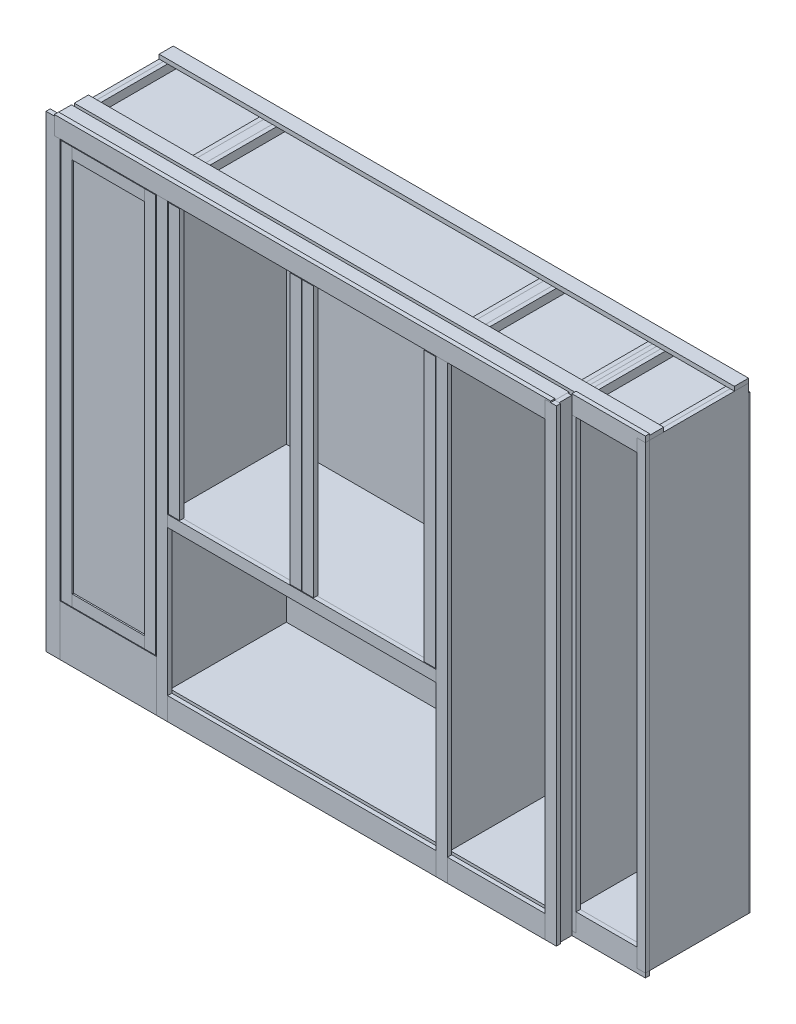
SolidWorks part; units mm, degrees
ref_plane "Front Plane" through (0, 0, 0) normal (0, 0, 1) x (1, 0, 0)
ref_plane "Top Plane" through (0, 0, 0) normal (0, 1, 0) x (1, 0, 0)
ref_plane "Right Plane" through (0, 0, 0) normal (1, 0, 0) x (0, 0, -1)
sketch "Sketch1" plane through (0, 0, 0) normal (0, 0, 1) x (1, 0, 0)
  line L0 (0, 0) -> (0, 1050.925) construction
  line L2 (-254, 19.05) -> (254, 19.05) construction
  line L3 (-254, 19.05) -> (-254, 2082.8) construction
  line L4 (-254, 2082.8) -> (254, 2082.8) construction
  line L5 (254, 19.05) -> (254, 2082.8) construction
  line L6 (-254, 19.05) -> (254, 2082.8) construction
  line L7 (-254, 2082.8) -> (254, 19.05) construction
  line L8 (-254, 2082.8) -> (-234.95, 2082.8)
  line L9 (-254, 2082.8) -> (-254, 19.05)
  line L10 (-254, 19.05) -> (-234.95, 19.05)
  line L11 (-234.95, 2082.8) -> (-234.95, 19.05)
  line L12 (254, 2082.8) -> (215.9, 2082.8)
  line L13 (254, 2082.8) -> (254, 19.05)
  line L14 (254, 19.05) -> (215.9, 19.05)
  line L15 (215.9, 2082.8) -> (215.9, 19.05)
  dimension "D1" = 19.05
  dimension "D2" = 2063.75
  dimension "D3" = 508
  dimension "D4" = 19.05
  dimension "D5" = 38.1
extrude "Boss-Extrude1" add sketch "Sketch1" against normal blind 520.7
sketch "Sketch2" plane through (0, 0, -520.7) normal (0, 0, -1) x (-1, 0, 0)
  line L1 (-215.9, 222.25) -> (-196.85, 222.25)
  line L2 (-215.9, 222.25) -> (-215.9, 19.05)
  line L3 (-215.9, 19.05) -> (-196.85, 19.05)
  line L4 (-196.85, 222.25) -> (-196.85, 19.05)
  line L6 (234.95, 19.05) -> (215.9, 19.05)
  line L7 (234.95, 19.05) -> (234.95, 222.25)
  line L8 (234.95, 222.25) -> (215.9, 222.25)
  line L9 (215.9, 19.05) -> (215.9, 222.25)
  dimension "D1" = 203.2
  dimension "D2" = 19.05
extrude "Boss-Extrude2" add sketch "Sketch2" against normal up to surface (520.7 mm away) separate body up to face at (-244.475, 1050.925, 0)
sketch "Sketch4" plane through (0, 0, -520.7) normal (0, 0, 1) x (1, 0, 0)
  line L1 (215.9, 222.25) -> (-234.95, 222.25)
  line L2 (215.9, 222.25) -> (215.9, 241.3)
  line L3 (215.9, 241.3) -> (-234.95, 241.3)
  line L4 (-234.95, 222.25) -> (-234.95, 241.3)
  dimension "D1" = 19.05
extrude "Boss-Extrude4" add sketch "Sketch4" along normal up to surface (520.7 mm away) separate body up to face at (234.95, 1050.925, 0)
sketch "Sketch5" plane through (0, 0, -520.7) normal (0, 0, 1) x (1, 0, 0)
  line L1 (215.9, 2082.8) -> (196.85, 2082.8)
  line L2 (215.9, 2082.8) -> (215.9, 2044.7)
  line L3 (215.9, 2044.7) -> (196.85, 2044.7)
  line L4 (196.85, 2082.8) -> (196.85, 2044.7)
  line L5 (-234.95, 2082.8) -> (-215.9, 2082.8)
  line L6 (-234.95, 2082.8) -> (-234.95, 2044.7)
  line L7 (-234.95, 2044.7) -> (-215.9, 2044.7)
  line L8 (-215.9, 2082.8) -> (-215.9, 2044.7)
  dimension "D1" = 19.05
  dimension "D2" = 38.1
extrude "Boss-Extrude5" add sketch "Sketch5" along normal up to surface (520.7 mm away) separate body up to face at (234.95, 1050.925, 0)
sketch "Sketch6" plane through (0, 0, -520.7) normal (0, 0, 1) x (1, 0, 0)
  line L1 (-234.95, 2044.7) -> (215.9, 2044.7)
  line L2 (-234.95, 2044.7) -> (-234.95, 2025.65)
  line L3 (-234.95, 2025.65) -> (215.9, 2025.65)
  line L4 (215.9, 2044.7) -> (215.9, 2025.65)
  dimension "D1" = 19.05
extrude "Boss-Extrude6" add sketch "Sketch6" along normal up to surface (520.7 mm away) separate body up to face at (234.95, 1050.925, 0)
sketch "Sketch8" plane through (0, 0, 0) normal (0, 0, 1) x (1, 0, 0)
  line L0 (1727.2, 0) -> (1727.2, 1050.925) construction
  line L1 (254, 19.05) -> (254, 2082.8) construction
  line L2 (1981.2, 19.05) -> (1473.2, 19.05) construction
  line L3 (1981.2, 19.05) -> (1981.2, 2082.8) construction
  line L4 (1981.2, 2082.8) -> (1473.2, 2082.8) construction
  line L5 (1473.2, 19.05) -> (1473.2, 2082.8) construction
  line L6 (1981.2, 19.05) -> (1473.2, 2082.8) construction
  line L7 (1981.2, 2082.8) -> (1473.2, 19.05) construction
  line L8 (3142.9795, 0) -> (-520.5672, 0) construction
  line L10 (1981.2, 2082.8) -> (1962.15, 2082.8)
  line L11 (1981.2, 2082.8) -> (1981.2, 19.05)
  line L12 (1981.2, 19.05) -> (1962.15, 19.05)
  line L13 (1962.15, 2082.8) -> (1962.15, 19.05)
  line L14 (1473.2, 2082.8) -> (1511.3, 2082.8)
  line L15 (1473.2, 2082.8) -> (1473.2, 19.05)
  line L16 (1473.2, 19.05) -> (1511.3, 19.05)
  line L17 (1511.3, 2082.8) -> (1511.3, 19.05)
  dimension "D1" = 19.05
  dimension "D2" = 508
  dimension "D3" = 1219.2
  dimension "D4" = 2063.75
  dimension "D5" = 19.05
  dimension "D6" = 38.1
extrude "Boss-Extrude7" add sketch "Sketch8" against normal blind 520.7 separate body
sketch "Sketch10" plane through (0, 0, -520.7) normal (0, 0, -1) x (-1, 0, 0)
  line L1 (-1530.35, 19.05) -> (-1511.3, 19.05)
  line L2 (-1530.35, 19.05) -> (-1530.35, 95.25)
  line L3 (-1530.35, 95.25) -> (-1511.3, 95.25)
  line L4 (-1511.3, 19.05) -> (-1511.3, 95.25)
  line L5 (-1943.1, 19.05) -> (-1962.15, 19.05)
  line L6 (-1943.1, 19.05) -> (-1943.1, 95.25)
  line L7 (-1943.1, 95.25) -> (-1962.15, 95.25)
  line L8 (-1962.15, 19.05) -> (-1962.15, 95.25)
  dimension "D1" = 19.05
  dimension "D2" = 76.2
extrude "Boss-Extrude8" add sketch "Sketch10" against normal up to surface (520.7 mm away) separate body up to face at (1971.675, 1050.925, 0)
sketch "Sketch12" plane through (0, 0, -520.7) normal (0, 0, -1) x (-1, 0, 0)
  line L1 (-1530.35, 2082.8) -> (-1511.3, 2082.8)
  line L2 (-1530.35, 2082.8) -> (-1530.35, 2044.7)
  line L3 (-1530.35, 2044.7) -> (-1511.3, 2044.7)
  line L4 (-1511.3, 2082.8) -> (-1511.3, 2044.7)
  line L5 (-1943.1, 2082.8) -> (-1962.15, 2082.8)
  line L6 (-1943.1, 2082.8) -> (-1943.1, 2044.7)
  line L7 (-1943.1, 2044.7) -> (-1962.15, 2044.7)
  line L8 (-1962.15, 2082.8) -> (-1962.15, 2044.7)
  dimension "D1" = 19.05
  dimension "D2" = 38.1
extrude "Boss-Extrude9" add sketch "Sketch12" against normal up to surface (520.7 mm away) separate body up to face at (1971.675, 1050.925, 0)
sketch "Sketch13" plane through (0, 0, -520.7) normal (0, 0, -1) x (-1, 0, 0)
  line L0 (-1962.15, 2082.8) -> (-1962.15, 19.05) construction
  line L1 (-1511.3, 95.25) -> (-1962.15, 95.25)
  line L2 (-1511.3, 95.25) -> (-1511.3, 114.3)
  line L3 (-1511.3, 114.3) -> (-1962.15, 114.3)
  line L4 (-1962.15, 95.25) -> (-1962.15, 114.3)
  dimension "D1" = 19.05
extrude "Boss-Extrude10" add sketch "Sketch13" against normal up to surface (520.7 mm away) separate body up to face at (1492.25, 1050.925, 0)
sketch "Sketch14" plane through (0, 0, -520.7) normal (0, 0, -1) x (-1, 0, 0)
  line L0 (-1962.15, 2082.8) -> (-1962.15, 19.05) construction
  line L1 (-1511.3, 2044.7) -> (-1962.15, 2044.7)
  line L2 (-1511.3, 2044.7) -> (-1511.3, 2025.65)
  line L3 (-1511.3, 2025.65) -> (-1962.15, 2025.65)
  line L4 (-1962.15, 2044.7) -> (-1962.15, 2025.65)
  dimension "D1" = 19.05
extrude "Boss-Extrude11" add sketch "Sketch14" against normal up to surface (520.7 mm away) separate body up to face at (1971.675, 1050.925, 0)
sketch "Sketch15" plane through (0, 0, -520.7) normal (0, 0, -1) x (-1, 0, 0)
  line L1 (-254, 19.05) -> (-273.05, 19.05)
  line L2 (-254, 19.05) -> (-254, 95.25)
  line L3 (-254, 95.25) -> (-273.05, 95.25)
  line L4 (-273.05, 19.05) -> (-273.05, 95.25)
  line L5 (-1473.2, 19.05) -> (-1454.15, 19.05)
  line L6 (-1473.2, 19.05) -> (-1473.2, 95.25)
  line L7 (-1473.2, 95.25) -> (-1454.15, 95.25)
  line L8 (-1454.15, 19.05) -> (-1454.15, 95.25)
  line L9 (-1473.2, 2082.8) -> (-1454.15, 2082.8)
  line L10 (-1473.2, 2082.8) -> (-1473.2, 2044.7)
  line L11 (-1473.2, 2044.7) -> (-1454.15, 2044.7)
  line L12 (-1454.15, 2082.8) -> (-1454.15, 2044.7)
  line L13 (-254, 2082.8) -> (-273.05, 2082.8)
  line L14 (-254, 2082.8) -> (-254, 2044.7)
  line L15 (-254, 2044.7) -> (-273.05, 2044.7)
  line L16 (-273.05, 2082.8) -> (-273.05, 2044.7)
  dimension "D1" = 19.05
  dimension "D2" = 38.1
  dimension "D3" = 76.2
extrude "Boss-Extrude12" add sketch "Sketch15" against normal up to surface (520.7 mm away) separate body up to face at (1492.25, 1050.925, 0)
sketch "Sketch16" plane through (0, 0, -520.7) normal (0, 0, -1) x (-1, 0, 0)
  line L0 (-254, 19.05) -> (-254, 2082.8) construction
  line L1 (-1473.2, 2044.7) -> (-254, 2044.7)
  line L2 (-1473.2, 2044.7) -> (-1473.2, 2025.65)
  line L3 (-1473.2, 2025.65) -> (-254, 2025.65)
  line L4 (-254, 2044.7) -> (-254, 2025.65)
  line L6 (-1473.2, 95.25) -> (-254, 95.25)
  line L7 (-1473.2, 95.25) -> (-1473.2, 114.3)
  line L8 (-1473.2, 114.3) -> (-254, 114.3)
  line L9 (-254, 95.25) -> (-254, 114.3)
  dimension "D1" = 19.05
  dimension "D2" = 19.05
extrude "Boss-Extrude13" add sketch "Sketch16" against normal up to surface (520.7 mm away) separate body up to face at (1492.25, 1050.925, 0)
sketch "Sketch17" plane through (0, 0, -520.7) normal (0, 0, -1) x (-1, 0, 0)
  line L0 (-254, 19.05) -> (-254, 2082.8) construction
  line L1 (-1473.2, 2025.65) -> (-254, 2025.65) construction
  line L2 (-1473.2, 2025.65) -> (-1473.2, 806.45) construction
  line L3 (-1473.2, 806.45) -> (-254, 806.45) construction
  line L4 (-254, 2025.65) -> (-254, 806.45) construction
  line L6 (-1473.2, 806.45) -> (-254, 806.45)
  line L7 (-1473.2, 806.45) -> (-1473.2, 787.4)
  line L8 (-1473.2, 787.4) -> (-254, 787.4)
  line L9 (-254, 806.45) -> (-254, 787.4)
  dimension "D1" = 1219.2
  dimension "D2" = 19.05
extrude "Boss-Extrude14" add sketch "Sketch17" against normal up to surface (520.7 mm away) separate body up to face at (1492.25, 1050.925, 0)
sketch "Sketch25" plane through (0, 0, -520.7) normal (0, 0, -1) x (-1, 0, 0)
  line L1 (-1981.2, 2082.8) -> (-2000.25, 2082.8)
  line L2 (-1981.2, 2082.8) -> (-1981.2, 19.05)
  line L3 (-1981.2, 19.05) -> (-2000.25, 19.05)
  line L4 (-2000.25, 2082.8) -> (-2000.25, 19.05)
  dimension "D1" = 19.05
extrude "Boss-Extrude22" add sketch "Sketch25" against normal blind 444.5 separate body
sketch "Sketch26" plane through (0, 0, -520.7) normal (0, 0, 1) x (1, 0, 0)
  line L1 (2000.25, 2082.8) -> (2330.45, 2082.8) construction
  line L2 (2000.25, 2082.8) -> (2000.25, 19.05) construction
  line L3 (2000.25, 19.05) -> (2330.45, 19.05) construction
  line L4 (2330.45, 2082.8) -> (2330.45, 19.05) construction
  line L5 (2330.45, 2082.8) -> (2311.4, 2082.8)
  line L6 (2330.45, 2082.8) -> (2330.45, 19.05)
  line L7 (2330.45, 19.05) -> (2311.4, 19.05)
  line L8 (2311.4, 2082.8) -> (2311.4, 19.05)
  dimension "D1" = 330.2
  dimension "D2" = 2063.75
  dimension "D3" = 19.05
extrude "Boss-Extrude23" add sketch "Sketch26" along normal blind 444.5 separate body
sketch "Sketch27" plane through (0, 0, -520.7) normal (0, 0, -1) x (-1, 0, 0)
  line L1 (-2000.25, 2082.8) -> (-2019.3, 2082.8)
  line L2 (-2000.25, 2082.8) -> (-2000.25, 2044.7)
  line L3 (-2000.25, 2044.7) -> (-2019.3, 2044.7)
  line L4 (-2019.3, 2082.8) -> (-2019.3, 2044.7)
  line L5 (-2311.4, 2082.8) -> (-2292.35, 2082.8)
  line L6 (-2311.4, 2082.8) -> (-2311.4, 2044.7)
  line L7 (-2311.4, 2044.7) -> (-2292.35, 2044.7)
  line L8 (-2292.35, 2082.8) -> (-2292.35, 2044.7)
  line L9 (-2000.25, 19.05) -> (-2019.3, 19.05)
  line L10 (-2000.25, 19.05) -> (-2000.25, 82.55)
  line L11 (-2000.25, 82.55) -> (-2019.3, 82.55)
  line L12 (-2019.3, 19.05) -> (-2019.3, 82.55)
  line L13 (-2311.4, 19.05) -> (-2292.35, 19.05)
  line L14 (-2311.4, 19.05) -> (-2311.4, 82.55)
  line L15 (-2311.4, 82.55) -> (-2292.35, 82.55)
  line L16 (-2292.35, 19.05) -> (-2292.35, 82.55)
  dimension "D1" = 19.05
  dimension "D2" = 38.1
  dimension "D3" = 63.5
extrude "Boss-Extrude24" add sketch "Sketch27" against normal up to surface (444.5 mm away) separate body up to face at (2320.925, 1050.925, -76.2)
sketch "Sketch28" plane through (0, 0, -520.7) normal (0, 0, -1) x (-1, 0, 0)
  line L0 (-2311.4, 2082.8) -> (-2311.4, 19.05) construction
  line L1 (-2000.25, 82.55) -> (-2311.4, 82.55)
  line L2 (-2000.25, 82.55) -> (-2000.25, 101.6)
  line L3 (-2000.25, 101.6) -> (-2311.4, 101.6)
  line L4 (-2311.4, 82.55) -> (-2311.4, 101.6)
  line L6 (-2000.25, 2044.7) -> (-2311.4, 2044.7)
  line L7 (-2000.25, 2044.7) -> (-2000.25, 2025.65)
  line L8 (-2000.25, 2025.65) -> (-2311.4, 2025.65)
  line L9 (-2311.4, 2044.7) -> (-2311.4, 2025.65)
  dimension "D1" = 19.05
extrude "Boss-Extrude25" add sketch "Sketch28" against normal up to surface (444.5 mm away) separate body up to face at (2320.925, 1050.925, -76.2)
sketch "Sketch19" plane through (0, 0, 0) normal (0, 0, 1) x (1, 0, 0)
  line L0 (1981.2, 19.05) -> (1981.2, 2082.8) construction
  line L1 (-254, 19.05) -> (1981.2, 19.05)
  line L2 (-254, 19.05) -> (-254, 0)
  line L3 (-254, 0) -> (1981.2, 0)
  line L4 (1981.2, 19.05) -> (1981.2, 0)
  line L8 (-254, 2082.8) -> (1981.2, 2082.8)
  line L9 (-254, 2082.8) -> (-254, 2101.85)
  line L10 (-254, 2101.85) -> (1981.2, 2101.85)
  line L11 (1981.2, 2082.8) -> (1981.2, 2101.85)
  dimension "D1" = 19.05
  dimension "D2" = 19.05
extrude "Boss-Extrude16" add sketch "Sketch19" against normal blind 63.5 separate body
sketch "Sketch20" plane through (0, 0, 0) normal (0, 0, 1) x (1, 0, 0)
  line L1 (-254, 2082.8) -> (-273.05, 2082.8)
  line L2 (-254, 2082.8) -> (-254, 0)
  line L3 (-254, 0) -> (-273.05, 0)
  line L4 (-273.05, 2082.8) -> (-273.05, 0)
  dimension "D1" = 19.05
extrude "Boss-Extrude17" add sketch "Sketch20" against normal blind 63.5 separate body
sketch "Sketch21" plane through (0, 0, 0) normal (0, 0, 1) x (1, 0, 0)
  line L0 (-234.95, 19.05) -> (-234.95, 2082.8) construction
  line L1 (-222.25, 2101.85) -> (-285.75, 2101.85)
  line L2 (-222.25, 2101.85) -> (-222.25, 0)
  line L3 (-222.25, 0) -> (-285.75, 0)
  line L4 (-285.75, 2101.85) -> (-285.75, 0)
  line L5 (-273.05, 0) -> (-254, 0) construction
  line L6 (1981.2, 2101.85) -> (-254, 2101.85) construction
  dimension "D1" = 12.7
  dimension "D2" = 63.5
extrude "Boss-Extrude18" add sketch "Sketch21" along normal blind 19.05 separate body
sketch "Sketch22" plane through (0, 0, 0) normal (0, 0, 1) x (1, 0, 0)
  line L0 (234.95, 1982.001) -> (234.95, 1850.1699) construction
  line L1 (254, 2082.8) -> (215.9, 2082.8) construction
  line L2 (1492.25, 2082.8) -> (1492.25, -47917.2) construction
  line L3 (1511.3, 2082.8) -> (1473.2, 2082.8) construction
  line L4 (1981.2, 2082.8) -> (1981.2, 52082.8) construction
  line L6 (-222.25, 0) -> (-222.25, 2101.85) construction
  line L7 (209.55, 0) -> (260.35, 0)
  line L8 (209.55, 0) -> (209.55, 2101.85)
  line L9 (209.55, 2101.85) -> (260.35, 2101.85)
  line L10 (260.35, 0) -> (260.35, 2101.85)
  line L11 (209.55, 0) -> (260.35, 2101.85) construction
  line L12 (209.55, 2101.85) -> (260.35, 0) construction
  line L13 (1466.85, 0) -> (1517.65, 0)
  line L14 (1466.85, 0) -> (1466.85, 2101.85)
  line L15 (1466.85, 2101.85) -> (1517.65, 2101.85)
  line L16 (1517.65, 0) -> (1517.65, 2101.85)
  line L17 (1466.85, 0) -> (1517.65, 2101.85) construction
  line L18 (1466.85, 2101.85) -> (1517.65, 0) construction
  line L19 (1955.8, 0) -> (2006.6, 0)
  line L20 (1955.8, 0) -> (1955.8, 2101.85)
  line L21 (1955.8, 2101.85) -> (2006.6, 2101.85)
  line L22 (2006.6, 0) -> (2006.6, 2101.85)
  line L23 (1955.8, 0) -> (2006.6, 2101.85) construction
  line L24 (1955.8, 2101.85) -> (2006.6, 0) construction
  line L25 (-254, 0) -> (1981.2, 0) construction
  line L28 (1981.2, 19.05) -> (1981.2, 2082.8) construction
  point P6 (1492.25, 2082.8)
  point P12 (234.95, 1050.925)
  point P17 (1492.25, 1050.925)
  point P22 (1981.2, 1050.925)
  point P27 (234.95, 2082.8)
  dimension "D1" = 50.8
  dimension "D2" = 0
  dimension "D4" = 25.4
extrude "Boss-Extrude19" add sketch "Sketch22" along normal blind 19.05 separate body
sketch "Sketch23" plane through (0, 0, 0) normal (0, 0, 1) x (1, 0, 0)
  line L0 (209.55, 0) -> (260.35, 0) construction
  line L1 (-273.05, 0) -> (234.95, 0)
  line L2 (-273.05, 0) -> (-273.05, 228.6)
  line L3 (-273.05, 228.6) -> (234.95, 228.6)
  line L4 (234.95, 0) -> (234.95, 228.6)
  point P5 (234.95, 0)
  dimension "D1" = 228.6
extrude "Boss-Extrude20" add sketch "Sketch23" along normal blind 19.05 separate body
sketch "Sketch24" plane through (0, 0, 0) normal (0, 0, 1) x (1, 0, 0)
  line L0 (209.55, 0) -> (260.35, 0) construction
  line L1 (234.95, 0) -> (1981.2, 0)
  line L2 (234.95, 0) -> (234.95, 101.6)
  line L3 (234.95, 101.6) -> (1981.2, 101.6)
  line L4 (1981.2, 0) -> (1981.2, 101.6)
  line L5 (1981.2, 19.05) -> (1981.2, 2082.8) construction
  line L6 (863.6, -193.55) -> (863.6, 49806.45) construction
  line L7 (1981.2, 2025.65) -> (-248.3733, 2025.65)
  line L8 (1981.2, 2025.65) -> (1981.2, 2108.2)
  line L9 (1981.2, 2108.2) -> (-248.3733, 2108.2)
  line L10 (-248.3733, 2025.65) -> (-248.3733, 2108.2)
  line L11 (2006.6, 2101.85) -> (1955.8, 2101.85) construction
  line L12 (-746, 781.05) -> (49254, 781.05) construction
  line L14 (254, 806.45) -> (1473.2, 806.45) construction
  line L15 (1492.25, 1082.8) -> (1492.25, 51082.8) construction
  line L16 (234.95, 755.65) -> (1492.25, 755.65)
  line L17 (234.95, 755.65) -> (234.95, 806.45)
  line L18 (234.95, 806.45) -> (1492.25, 806.45)
  line L19 (1492.25, 755.65) -> (1492.25, 806.45)
  line L20 (234.95, 755.65) -> (1492.25, 806.45) construction
  line L21 (234.95, 806.45) -> (1492.25, 755.65) construction
  line L22 (1511.3, 2082.8) -> (1473.2, 2082.8) construction
  line L23 (234.95, 1082.8) -> (234.95, 51082.8) construction
  line L24 (254, 2082.8) -> (215.9, 2082.8) construction
  point P12 (1981.2, 2101.85)
  point P21 (863.6, 781.05)
  point P25 (863.6, 806.45)
  point P35 (1492.25, 2082.8)
  point P40 (234.95, 2082.8)
  dimension "D1" = 101.6
  dimension "D2" = 0
  dimension "D3" = 82.55
  dimension "D4" = 50.8
  dimension "D5" = 0
extrude "Boss-Extrude21" add sketch "Sketch24" along normal blind 19.05 separate body
sketch "Sketch29" plane through (0, 0, -76.2) normal (0, 0, 1) x (1, 0, 0)
  line L6 (2330.45, 2082.8) -> (2292.35, 2082.8)
  line L7 (2330.45, 2082.8) -> (2330.45, 19.05)
  line L8 (2330.45, 19.05) -> (2292.35, 19.05)
  line L9 (2292.35, 2082.8) -> (2292.35, 19.05)
  line L10 (1981.2, 2082.8) -> (2019.3, 2082.8)
  line L11 (1981.2, 2082.8) -> (1981.2, 19.05)
  line L12 (1981.2, 19.05) -> (2019.3, 19.05)
  line L13 (2019.3, 2082.8) -> (2019.3, 19.05)
  dimension "D1" = 38.1
extrude "Boss-Extrude26" add sketch "Sketch29" along normal blind 19.05 separate body
sketch "Sketch30" plane through (0, 0, -76.2) normal (0, 0, 1) x (1, 0, 0)
  line L1 (2000.25, 2025.65) -> (2330.45, 2025.65)
  line L2 (2000.25, 2025.65) -> (2000.25, 2108.2)
  line L3 (2000.25, 2108.2) -> (2330.45, 2108.2)
  line L4 (2330.45, 2025.65) -> (2330.45, 2108.2)
  line L5 (2000.25, 101.6) -> (2330.45, 101.6)
  line L6 (2000.25, 101.6) -> (2000.25, 0)
  line L7 (2000.25, 0) -> (2330.45, 0)
  line L8 (2330.45, 101.6) -> (2330.45, 0)
  line L9 (2330.45, 19.05) -> (2330.45, 2082.8) construction
  line L10 (2330.45, 19.05) -> (2330.45, 2082.8) construction
  dimension "D1" = 101.6
  dimension "D2" = 82.55
extrude "Boss-Extrude27" add sketch "Sketch30" along normal blind 19.05 separate body
sketch "Sketch31" plane through (1981.2, 0, 0) normal (1, 0, 0) x (0, 0, -1)
  line L1 (0, 2101.85) -> (57.15, 2101.85)
  line L2 (0, 2101.85) -> (0, 0)
  line L3 (0, 0) -> (57.15, 0)
  line L4 (57.15, 2101.85) -> (57.15, 0)
extrude "Boss-Extrude28" add sketch "Sketch31" along normal blind 19.05 separate body
sketch "Sketch33" plane through (0, 0, 0) normal (0, 0, 1) x (1, 0, 0)
  line L0 (-248.3733, 2025.65) -> (1981.2, 2025.65) construction
  line L1 (-222.25, 2025.65) -> (209.55, 2025.65) construction
  line L2 (-222.25, 2025.65) -> (-222.25, 228.6) construction
  line L3 (-222.25, 228.6) -> (209.55, 228.6) construction
  line L4 (209.55, 2025.65) -> (209.55, 228.6) construction
  line L5 (-222.25, 0) -> (-222.25, 2101.85) construction
  line L6 (209.55, 2101.85) -> (209.55, 0) construction
  line L7 (234.95, 228.6) -> (-273.05, 228.6) construction
  line L8 (-219.075, 2022.475) -> (206.375, 2022.475) construction
  line L9 (206.375, 2022.475) -> (206.375, 231.775) construction
  line L10 (-219.075, 231.775) -> (206.375, 231.775) construction
  line L11 (-219.075, 2022.475) -> (-219.075, 231.775) construction
  line L13 (-219.075, 2022.475) -> (-168.275, 2022.475)
  line L14 (-219.075, 2022.475) -> (-219.075, 231.775)
  line L15 (-219.075, 231.775) -> (-168.275, 231.775)
  line L16 (-168.275, 2022.475) -> (-168.275, 231.775)
  line L17 (206.375, 231.775) -> (155.575, 231.775)
  line L18 (206.375, 231.775) -> (206.375, 2022.475)
  line L19 (206.375, 2022.475) -> (155.575, 2022.475)
  line L20 (155.575, 231.775) -> (155.575, 2022.475)
  dimension "D2" = 50.8
  dimension "D1" = 3.175
extrude "Boss-Extrude29" add sketch "Sketch33" along normal blind 19.05 separate body
sketch "Sketch34" plane through (0, 0, 0) normal (0, 0, 1) x (1, 0, 0)
  line L1 (-180.975, 2022.475) -> (168.275, 2022.475)
  line L2 (-180.975, 2022.475) -> (-180.975, 1971.675)
  line L3 (-180.975, 1971.675) -> (168.275, 1971.675)
  line L4 (168.275, 2022.475) -> (168.275, 1971.675)
  line L6 (-180.975, 231.775) -> (168.275, 231.775)
  line L7 (-180.975, 231.775) -> (-180.975, 282.575)
  line L8 (-180.975, 282.575) -> (168.275, 282.575)
  line L9 (168.275, 231.775) -> (168.275, 282.575)
  line L10 (-168.275, 231.775) -> (-168.275, 2022.475) construction
  line L11 (155.575, 2022.475) -> (155.575, 231.775) construction
  dimension "D1" = 50.8
  dimension "D2" = 12.7
  dimension "D3" = 12.7
extrude "Boss-Extrude30" add sketch "Sketch34" along normal blind 19.05 separate body
sketch "Sketch36" plane through (0, 2022.475, 0) normal (0, 1, 0) x (1, 0, 0)
  line L0 (-168.275, -19.05) -> (-168.275, 0) construction
  line L1 (-168.275, -6.35) -> (-180.975, -6.35)
  line L2 (-168.275, -6.35) -> (-168.275, -12.7)
  line L3 (-168.275, -12.7) -> (-180.975, -12.7)
  line L4 (-180.975, -6.35) -> (-180.975, -12.7)
  line L5 (-1168.275, -9.525) -> (48831.725, -9.525) construction
  line L6 (-6.35, -19.05) -> (-6.35, 0) construction
  line L7 (168.275, -19.05) -> (-180.975, -19.05) construction
  line L8 (168.275, 0) -> (-180.975, 0) construction
  line L9 (168.275, -6.35) -> (168.275, -12.7)
  line L10 (155.575, -12.7) -> (168.275, -12.7)
  line L11 (155.575, -6.35) -> (155.575, -12.7)
  line L12 (155.575, -6.35) -> (168.275, -6.35)
  point P9 (-168.275, -9.525)
  dimension "D1" = 6.35
  dimension "D2" = 12.7
extrude "Cut-Extrude1" cut sketch "Sketch36" against normal through all
sketch "Sketch37" plane through (0, 2022.475, 0) normal (0, 1, 0) x (1, 0, 0)
  line L1 (-168.275, -6.35) -> (-180.975, -6.35)
  line L2 (-168.275, -6.35) -> (-168.275, 0)
  line L3 (-168.275, 0) -> (-180.975, 0)
  line L4 (-180.975, -6.35) -> (-180.975, 0)
  line L6 (-168.275, -12.7) -> (-180.975, -12.7)
  line L7 (-168.275, -12.7) -> (-168.275, -19.05)
  line L8 (-168.275, -19.05) -> (-180.975, -19.05)
  line L9 (-180.975, -12.7) -> (-180.975, -19.05)
  line L10 (-180.975, -6.35) -> (-180.975, -12.7) construction
  line L12 (168.275, 0) -> (-180.975, 0) construction
  line L13 (168.275, -19.05) -> (-180.975, -19.05) construction
  line L14 (-6.35, -19.05) -> (-6.35, 0) construction
  line L15 (168.275, -12.7) -> (168.275, -19.05)
  line L16 (155.575, -19.05) -> (168.275, -19.05)
  line L17 (155.575, -12.7) -> (155.575, -19.05)
  line L18 (155.575, -12.7) -> (168.275, -12.7)
  line L19 (168.275, -6.35) -> (168.275, 0)
  line L20 (155.575, 0) -> (168.275, 0)
  line L21 (155.575, -6.35) -> (155.575, 0)
  line L22 (155.575, -6.35) -> (168.275, -6.35)
extrude "Cut-Extrude2" cut sketch "Sketch37" against normal through all
sketch "Sketch39" plane through (-180.975, 0, 0) normal (-1, 0, 0) x (0, 0, 1)
  line L0 (6.35, 1971.675) -> (6.35, 2022.475) construction
  line L1 (12.7, 1971.675) -> (6.35, 1971.675)
  line L2 (12.7, 1971.675) -> (12.7, 1984.375)
  line L3 (12.7, 1984.375) -> (6.35, 1984.375)
  line L4 (6.35, 1971.675) -> (6.35, 1984.375)
  line L5 (6.35, 231.775) -> (6.35, 282.575) construction
  line L6 (12.7, 282.575) -> (6.35, 282.575)
  line L7 (12.7, 282.575) -> (12.7, 269.875)
  line L8 (12.7, 269.875) -> (6.35, 269.875)
  line L9 (6.35, 282.575) -> (6.35, 269.875)
  dimension "D1" = 12.7
  dimension "D2" = 12.7
extrude "Cut-Extrude3" cut sketch "Sketch39" against normal through all
sketch "Sketch40" plane through (0, 0, 6.35) normal (0, 0, -1) x (-1, 0, 0)
  line L1 (180.975, 1984.375) -> (-168.275, 1984.375)
  line L2 (180.975, 1984.375) -> (180.975, 269.875)
  line L3 (180.975, 269.875) -> (-168.275, 269.875)
  line L4 (-168.275, 1984.375) -> (-168.275, 269.875)
extrude "Boss-Extrude31" add sketch "Sketch40" against normal up to surface (6.35 mm away) separate body up to face at (-6.35, 276.225, 12.7)
sketch "Sketch41" plane through (0, 0, -520.7) normal (0, 0, -1) x (-1, 0, 0)
  line L0 (254, 2082.8) -> (254, 19.05) construction
  line L1 (254, 2044.7) -> (-2330.45, 2044.7)
  line L2 (254, 2044.7) -> (254, 19.05)
  line L3 (254, 19.05) -> (-2330.45, 19.05)
  line L4 (-2330.45, 2044.7) -> (-2330.45, 19.05)
  line L5 (-2330.45, 19.05) -> (-2330.45, 2082.8) construction
extrude "Boss-Extrude32" add sketch "Sketch41" along normal blind 6.35 separate body
sketch "Sketch42" plane through (0, 2082.8, 0) normal (0, 1, 0) x (1, 0, 0)
  line L0 (2330.45, 76.2) -> (2330.45, 520.7) construction
  line L1 (-254, 520.7) -> (2330.45, 520.7)
  line L2 (-254, 520.7) -> (-254, 457.2)
  line L3 (-254, 457.2) -> (2330.45, 457.2)
  line L4 (2330.45, 520.7) -> (2330.45, 457.2)
  line L5 (-254, 520.7) -> (-254, 0) construction
  line L6 (2330.45, 76.2) -> (-254, 76.2)
  line L7 (2330.45, 76.2) -> (2330.45, 139.7)
  line L8 (2330.45, 139.7) -> (-254, 139.7)
  line L9 (-254, 76.2) -> (-254, 139.7)
  dimension "D1" = 63.5
extrude "Boss-Extrude33" add sketch "Sketch42" along normal blind 19.05 separate body
sketch "Sketch43" plane through (0, 0, 0) normal (0, 0, 1) x (1, 0, 0)
  line L0 (260.35, 0) -> (260.35, 2101.85) construction
  line L1 (260.35, 2025.65) -> (1466.85, 2025.65) construction
  line L2 (260.35, 2025.65) -> (260.35, 806.45) construction
  line L3 (260.35, 806.45) -> (1466.85, 806.45) construction
  line L4 (1466.85, 2025.65) -> (1466.85, 806.45) construction
  line L5 (-248.3733, 2025.65) -> (1981.2, 2025.65) construction
  line L6 (254, 806.45) -> (1473.2, 806.45) construction
  line L7 (1466.85, 2101.85) -> (1466.85, 0) construction
  line L8 (263.525, 2022.475) -> (263.525, 809.625) construction
  line L9 (263.525, 809.625) -> (1463.675, 809.625) construction
  line L10 (1463.675, 2022.475) -> (1463.675, 809.625) construction
  line L11 (263.525, 2022.475) -> (1463.675, 2022.475) construction
  line L13 (1463.675, 2022.475) -> (1412.875, 2022.475)
  line L14 (1463.675, 2022.475) -> (1463.675, 809.625)
  line L15 (1463.675, 809.625) -> (1412.875, 809.625)
  line L16 (1412.875, 2022.475) -> (1412.875, 809.625)
  line L17 (263.525, 2022.475) -> (314.325, 2022.475)
  line L18 (263.525, 2022.475) -> (263.525, 809.625)
  line L19 (263.525, 809.625) -> (314.325, 809.625)
  line L20 (314.325, 2022.475) -> (314.325, 809.625)
  dimension "D2" = 50.8
  dimension "D1" = 3.175
extrude "Boss-Extrude34" add sketch "Sketch43" along normal blind 19.05 separate body
sketch "Sketch44" plane through (0, 0, 0) normal (0, 0, 1) x (1, 0, 0)
  line L0 (863.6, -193.55) -> (863.6, 49806.45) construction
  line L1 (1492.25, 806.45) -> (234.95, 806.45) construction
  line L4 (865.1875, -193.55) -> (865.1875, 49806.45) construction
  line L5 (862.0125, -193.55) -> (862.0125, 49806.45) construction
  line L7 (314.325, 2022.475) -> (1412.875, 2022.475) construction
  line L8 (314.325, 2022.475) -> (314.325, 809.625) construction
  line L9 (314.325, 809.625) -> (1412.875, 809.625) construction
  line L10 (1412.875, 2022.475) -> (1412.875, 809.625) construction
  line L11 (862.0125, 2022.475) -> (811.2125, 2022.475)
  line L12 (862.0125, 2022.475) -> (862.0125, 809.625)
  line L13 (862.0125, 809.625) -> (811.2125, 809.625)
  line L14 (811.2125, 2022.475) -> (811.2125, 809.625)
  line L15 (865.1875, 2022.475) -> (915.9875, 2022.475)
  line L16 (865.1875, 2022.475) -> (865.1875, 809.625)
  line L17 (865.1875, 809.625) -> (915.9875, 809.625)
  line L18 (915.9875, 2022.475) -> (915.9875, 809.625)
  point P5 (863.6, 806.45)
  dimension "D1" = 1.5875
  dimension "D3" = 50.8
  dimension "D2" = 1.5875
extrude "Boss-Extrude35" add sketch "Sketch44" along normal blind 19.05 separate body
equation "\"ply_cabinet_thickness\"= 0.75"
equation "\"ply_shaker_door_panel\"= 0.25"
equation "\"ply_drawers\"= 0.5"
equation "\"cabinet_depth\"= 21.5 - 0.75 - 0.25'1/4 backandface frame"
equation "\"cabinet_back_thickness\"= 0.25"
equation "\"1.5_ledger\"= 1.5"
equation "\"Height-frames\"= 82.75 - .75 - .75"
equation "\"D1@Boss-Extrude7\"=\"cabinet_depth\""
equation "\"D1@Boss-Extrude1\"=\"cabinet_depth\""
equation "\"3_ledger\"= 3"
equation "\"D2@Sketch10\"=\"3_ledger\""
equation "\"D1@Sketch10\"=\"ply_cabinet_thickness\""
equation "\"D4@Sketch1\"=\"ply_cabinet_thickness\""
equation "\"left_cabinet_width\"= 20"
equation "\"right_cabinet_width\"= 20"
equation "\"D3@Sketch1\"=\"left_cabinet_width\""
equation "\"D2@Sketch1\"=\"Height-frames\""
equation "\"D2@Sketch2\"=\"ply_cabinet_thickness\""
equation "\"D1@Sketch4\"=\"ply_cabinet_thickness\""
equation "\"D1@Sketch5\"=\"ply_cabinet_thickness\""
equation "\"D2@Sketch5\"=\"1.5_ledger\""
equation "\"D1@Sketch6\"=\"ply_cabinet_thickness\""
equation "\"D4@Sketch8\"=\"Height-frames\""
equation "\"D2@Sketch8\"=\"right_cabinet_width\""
equation "\"D5@Sketch8\"=\"ply_cabinet_thickness\""
equation "\"D1@Sketch12\"=\"ply_cabinet_thickness\""
equation "\"D2@Sketch12\"=\"1.5_ledger\""
equation "\"D1@Sketch13\"=\"ply_cabinet_thickness\""
equation "\"D1@Sketch14\"=\"ply_cabinet_thickness\""
equation "\"D1@Sketch15\"=\"ply_cabinet_thickness\""
equation "\"D1@Sketch16\"=\"ply_cabinet_thickness\""
equation "\"D2@Sketch16\"=\"ply_cabinet_thickness\""
equation "\"D2@Sketch17\"=\"ply_cabinet_thickness\""
equation "\"D1@Boss-Extrude18\"=\"ply_cabinet_thickness\""
equation "\"2_face_frame_width\"= 2"
equation "\"D1@Sketch22\"=\"2_face_frame_width\""
equation "\"D4@Sketch24\"=\"2_face_frame_width\""
equation "\"D1@Sketch25\"=\"ply_cabinet_thickness\""
equation "\"bookcase_width\"= 13"
equation "\"D1@Sketch26\"=\"bookcase_width\""
equation "\"D2@Sketch26\"=\"Height-frames\""
equation "\"D3@Sketch26\"=\"ply_cabinet_thickness\""
equation "\"D1@Sketch27\"=\"ply_cabinet_thickness\""
equation "\"D2@Sketch27\"=\"1.5_ledger\""
equation "\"D1@Sketch28\"=\"ply_cabinet_thickness\""
equation "\"book_case_depth\"= 18.5 - 0.75 - 0.25"
equation "\"D1@Boss-Extrude23\"=\"book_case_depth\""
equation "\"shaker_door_stile_width\"= 2"
equation "\"shaker_door_rail_width\"= 2"
equation "\"shaker_door_panel_thickness\"=0.25"
equation "\"D2@Sketch33\"=\"shaker_door_stile_width\""
equation "\"D1@Boss-Extrude29\"=\"ply_cabinet_thickness\""
equation "\"D1@Sketch34\"=\"shaker_door_rail_width\""
equation "\"D1@Boss-Extrude30\"=\"ply_cabinet_thickness\""
equation "\"tongue_groove_depth\"= 0.5"
equation "\"D2@Sketch34\"=\"tongue_groove_depth\""
equation "\"D3@Sketch34\"=\"tongue_groove_depth\""
equation "\"D2@Sketch36\"=\"tongue_groove_depth\""
equation "\"D1@Sketch39\"=\"tongue_groove_depth\""
equation "\"D2@Sketch39\"=\"tongue_groove_depth\""
equation "\"D1@Boss-Extrude32\"=\"cabinet_back_thickness\""
equation "\"ply_cabinet_thickness_double\"= 1.5"
equation "\"D1@Boss-Extrude22\"=\"book_case_depth\""
equation "\"D6@Sketch8\"=\"ply_cabinet_thickness_double\""
equation "\"D5@Sketch1\"=\"ply_cabinet_thickness_double\""
equation "\"D2@Sketch43\"=\"shaker_door_stile_width\""
equation "\"D1@Boss-Extrude34\"=\"ply_cabinet_thickness\""
equation "\"D3@Sketch44\"=\"shaker_door_stile_width\""
equation "\"D1@Boss-Extrude35\"=\"ply_cabinet_thickness\""
